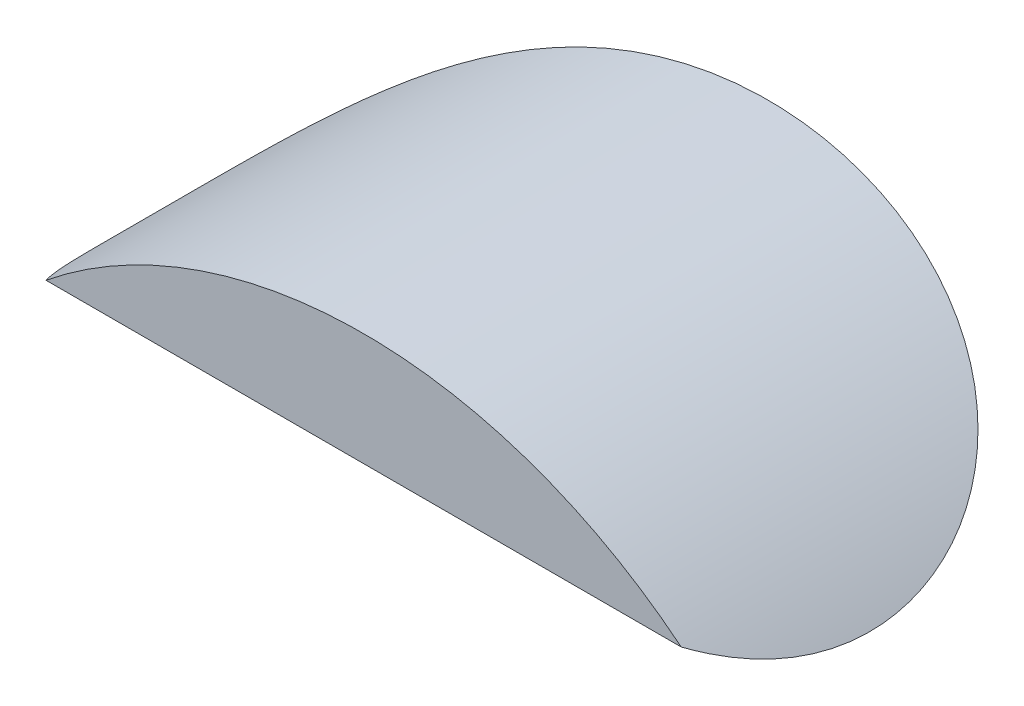
SolidWorks part; units mm, degrees
ref_plane "Front Plane" through (0, 0, 0) normal (0, 0, 1) x (1, 0, 0)
ref_plane "Top Plane" through (0, 0, 0) normal (0, 1, 0) x (1, 0, 0)
ref_plane "Right Plane" through (0, 0, 0) normal (1, 0, 0) x (0, 0, -1)
sketch "Sketch1" plane through (0, 0, 0) normal (1, 0, 0) x (0, 0, -1)
  circle A0 centre (0, 0) radius 11.75
  dimension "D1" = 23.5
extrude "Boss-Extrude1" add sketch "Sketch1" along normal blind 60
sketch "Sketch2" plane through (0, 0, 0) normal (-1, 0, 0) x (0, 0, 1)
  line L0 (5.8, 10.2187) -> (5.8, -10.2187)
  circle A0 centre (0, 0) radius 11.75 construction
  arc A1 (5.8, -10.2187) -> (5.8, 10.2187) centre (0, 0) ccw
  dimension "D1" = 5.8
extrude "Cut-Extrude1" cut sketch "Sketch2" against normal through all
sketch "Sketch3" plane through (0, 0, 5.8) normal (0, 0, 1) x (1, 0, 0)
  line L0 (30, -11.75) -> (30, 11.75) construction
  line L1 (60, 11.75) -> (0, 11.75) construction
  line L2 (0, -11.75) -> (60, -11.75) construction
  line L3 (0, -11.75) -> (60, -11.75) construction
  line L4 (60, 11.75) -> (0, 11.75) construction
  line L5 (0, 11.75) -> (60, 11.75)
  line L6 (60, 11.75) -> (60, -11.75)
  line L7 (60, -11.75) -> (44.2829, -11.75)
  line L8 (0, 11.75) -> (0, -11.75)
  line L9 (0, -11.75) -> (15.7171, -11.75)
  arc A0 (15.7171, -11.75) -> (44.2829, -11.75) centre (30, -25.75) cw
  point P8 (30, -11.75)
  point P10 (30, -5.75)
  dimension "D1" = 20
  dimension "D2" = 6
extrude "Cut-Extrude2" cut sketch "Sketch3" against normal through all
